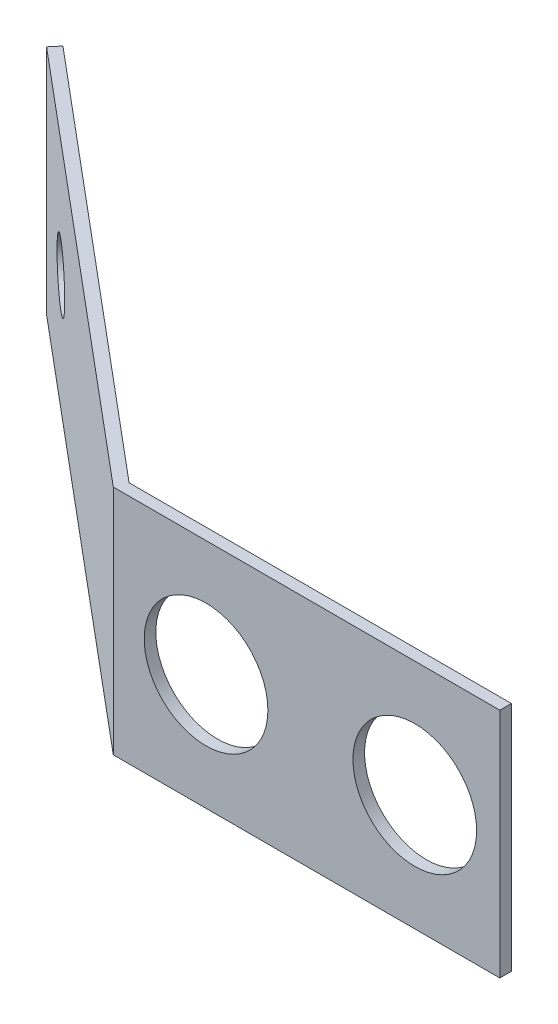
SolidWorks part; units mm, degrees
material "Perspex (TM) GS Acrylic Cast Sheet"
ref_plane "Front Plane" through (0, 0, 0) normal (0, 0, 1) x (1, 0, 0)
ref_plane "Top Plane" through (0, 0, 0) normal (0, 1, 0) x (1, 0, 0)
ref_plane "Right Plane" through (0, 0, 0) normal (1, 0, 0) x (0, 0, -1)
sketch "Sketch1" plane through (0, 0, 0) normal (0, 1, 0) x (1, 0, 0)
  line L0 (0, 0) -> (50, 0)
  line L1 (-16.5, 0) -> (16.5, 0) construction
  line L2 (0, 0) -> (-53.6231, 44.9951)
  dimension "D1" = 140
  dimension "D2" = 70
  dimension "D3" = 50
extrude "Extrude-Thin1" add sketch "Sketch1" along normal blind 30 thin thin type one direction wall 1.5
sketch "Sketch2" plane through (0, 0, 0) normal (-0.6428, 0, 0.766) x (0.766, 0, 0.6428)
  line L0 (-70, 30) -> (-70, 0) construction
  line L1 (19.9645, 0) -> (-19.9645, 0) construction
  circle A0 centre (-55, 15) radius 4
  dimension "D1" = 8
  dimension "D2" = 15
  dimension "D3" = 15
extrude "Cut-Extrude1" cut sketch "Sketch2" against normal blind 10
sketch "Sketch3" plane through (0, 0, 0) normal (0, 0, 1) x (1, 0, 0)
  line L1 (0, 30) -> (0, 0) construction
  line L2 (19.9645, 0) -> (-19.9645, 0) construction
  circle A0 centre (12, 15) radius 8
  circle A1 centre (39, 15) radius 8
  dimension "D1" = 16
  dimension "D2" = 27
  dimension "D3" = 12
  dimension "D4" = 15
extrude "Cut-Extrude2" cut sketch "Sketch3" against normal blind 10
